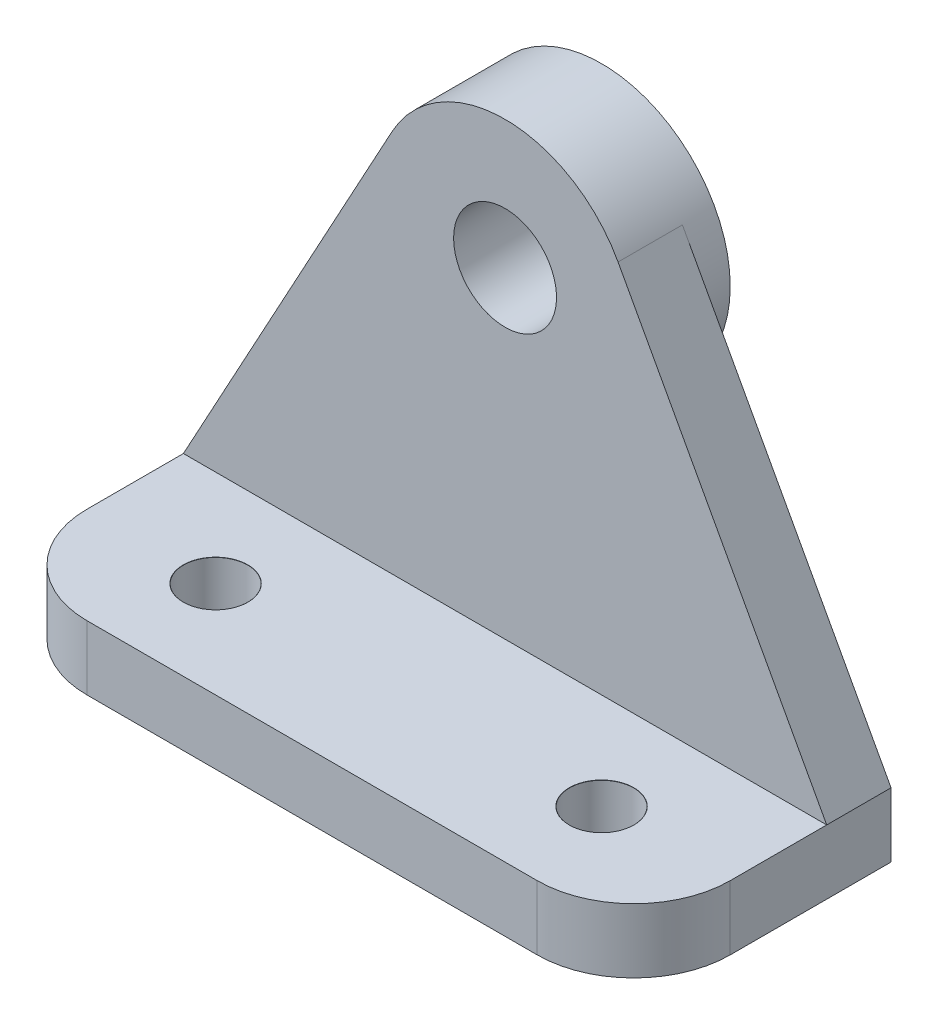
SolidWorks part; units mm, degrees
material "AISI 304"
ref_plane "Front Plane" through (0, 0, 0) normal (0, 0, 1) x (1, 0, 0)
ref_plane "Top Plane" through (0, 0, 0) normal (0, 1, 0) x (1, 0, 0)
ref_plane "Right Plane" through (0, 0, 0) normal (1, 0, 0) x (0, 0, -1)
sketch "Croquis1" plane through (0, 0, 0) normal (0, 1, 0) x (1, 0, 0)
  line L0 (50, 0) -> (-50, 0)
  line L1 (-50, 0) -> (-50, 40)
  line L2 (-50, 40) -> (50, 40)
  line L3 (50, 40) -> (50, 0)
  point P4 (0, 0)
  dimension "D1" = 100
  dimension "D2" = 40
extrude "Saliente-Extruir1" add sketch "Croquis1" along normal blind 10
sketch "Croquis2" plane through (0, 0, -40) normal (0, 0, -1) x (-1, 0, 0)
  line L0 (0, 10) -> (0, 60) construction
  line L1 (-50, 10) -> (50, 10) construction
  line L2 (-17.5647, 69.5647) -> (-50, 10)
  line L3 (17.5647, 69.5647) -> (50, 10)
  line L4 (-50, 10) -> (50, 10)
  arc A0 (-17.5647, 69.5647) -> (17.5647, 69.5647) centre (0, 60) cw
  circle A1 centre (0, 60) radius 8
  dimension "D2" = 20
  dimension "D3" = 16
  dimension "D1" = 50
extrude "Saliente-Extruir2" add sketch "Croquis2" against normal blind 10
sketch "Croquis3" plane through (0, 0, -30) normal (0, 0, 1) x (1, 0, 0)
  circle A0 centre (0, 60) radius 20
  circle A1 centre (0, 60) radius 8
extrude "Saliente-Extruir3" add sketch "Croquis3" against normal blind 15
sketch "Croquis4" plane through (0, 10, 0) normal (0, 1, 0) x (1, 0, 0)
  line L0 (-50, 0) -> (50, 0) construction
  line L2 (17.5647, 40) -> (50, 40) construction
  circle A0 centre (30, 15) radius 6.6071
  point P0 (30, 15)
  point P4 (0, 0)
  dimension "D1" = 30
  dimension "D2" = 25
hole_wizard "Ø10.0 (10) Diameter Hole1" positions "Croquis4" profile "Croquis5" hole size "Ø10.0" standard "ANSI Metric" end condition through all
sketch "Croquis5" plane through (30, 10, -15) normal (1, 0, 0) x (0, 0, 1)
  line L0 (0, 0) -> (0, 10)
  line L1 (0, 10) -> (5, 10)
  line L2 (5, 10) -> (5, 0.021)
  line L3 (5, 0.021) -> (5.025, 0)
  line L5 (5.025, 0) -> (0, 0)
  line L6 (-5, 0.021) -> (-5.025, 0) construction
  line L11 (0, -6.35) -> (0, 107.95) construction
  dimension "Thru Hole Dia." = 10
  dimension "Thru Hole Depth" = 10
  dimension "Near C'Sink Dia." = 10.05
  dimension "Near C'Sink Angle" = 100
sketch "Croquis6" plane through (0, 10, 0) normal (0, 1, 0) x (1, 0, 0)
  line L0 (-50, 40) -> (-17.5647, 40) construction
  circle A0 centre (-30, 15) radius 4.6265
  point P0 (-30, 15)
  dimension "D1" = 25
  dimension "D2" = 30
hole_wizard "Ø10.0 (10) Diameter Hole2" positions "Croquis6" profile "Croquis7" hole size "Ø10.0" standard "ANSI Metric" end condition through all
sketch "Croquis7" plane through (-30, 10, -15) normal (1, 0, 0) x (0, 0, 1)
  line L0 (0, 0) -> (0, 10)
  line L1 (0, 10) -> (5, 10)
  line L2 (5, 10) -> (5, 0.021)
  line L3 (5, 0.021) -> (5.025, 0)
  line L5 (5.025, 0) -> (0, 0)
  line L6 (-5, 0.021) -> (-5.025, 0) construction
  line L11 (0, -6.35) -> (0, 107.95) construction
  dimension "Thru Hole Dia." = 10
  dimension "Thru Hole Depth" = 10
  dimension "Near C'Sink Dia." = 10.05
  dimension "Near C'Sink Angle" = 100
fillet "Redondeo2" radius 15 2 edges at (50, 5, 0) (-50, 5, 0)
